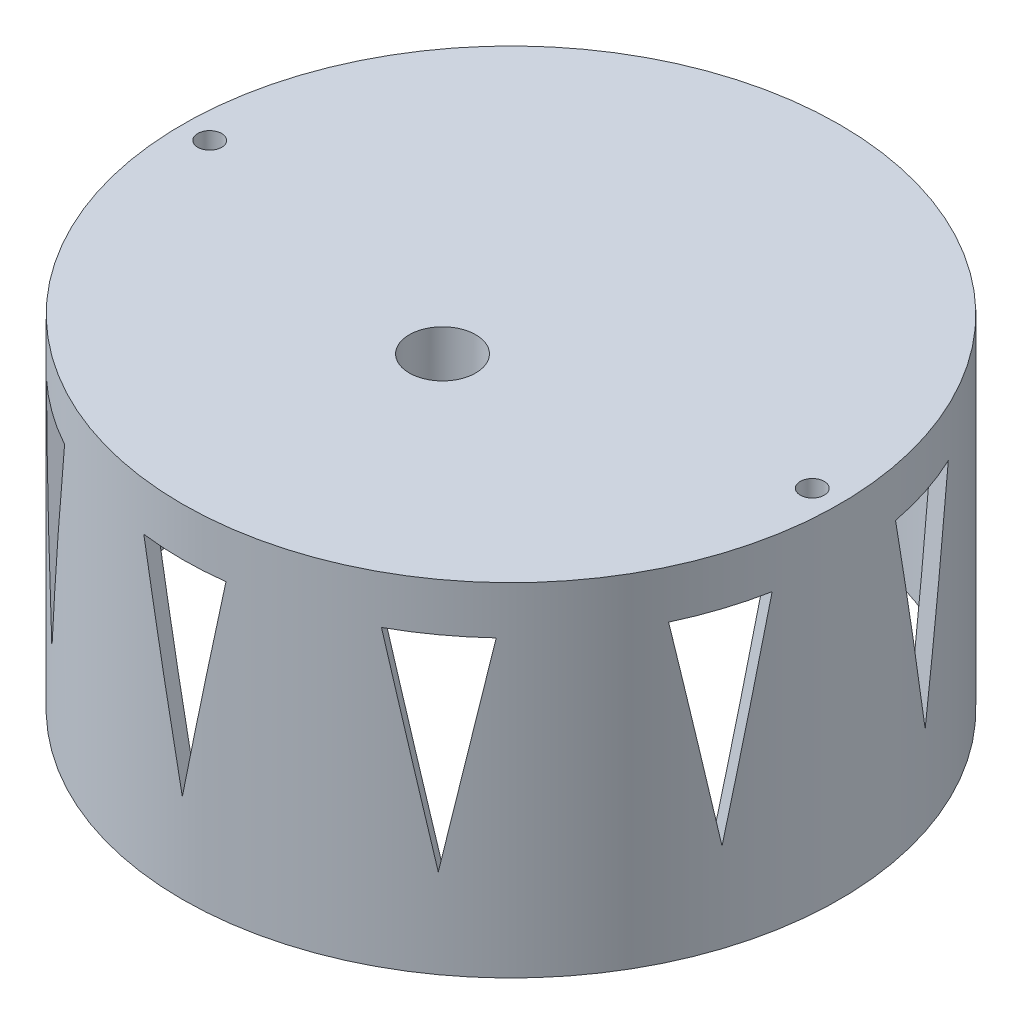
SolidWorks part; units mm, degrees
material "ABS"
ref_plane "Спереди" through (0, 0, 0) normal (0, 0, 1) x (1, 0, 0)
ref_plane "Сверху" through (0, 0, 0) normal (0, 1, 0) x (1, 0, 0)
ref_plane "Справа" through (0, 0, 0) normal (1, 0, 0) x (0, 0, -1)
sketch "Эскиз2" plane through (0, 0, 0) normal (0, 0, 1) x (1, 0, 0)
  line L0 (0, 0) -> (0, 74.988) construction
  line L1 (0, 0) -> (-48, 0)
  line L2 (-48, 0) -> (-48, -50)
  line L3 (-48, -50) -> (-46, -50)
  line L4 (-46, -50) -> (-46, -5.5)
  line L5 (-43, -2.5) -> (0, -2.5)
  line L6 (0, -2.5) -> (0, 0)
  arc A0 (-46, -5.5) -> (-43, -2.5) centre (-43, -5.5) cw
  dimension "D5" = 3
  dimension "D1" = 48
  dimension "D2" = 50
  dimension "D3" = 2
  dimension "D4" = 2.5
revolve "Основа" add sketch "Эскиз2" angle 360 about L0
sketch "Эскиз3" plane through (0, 0, 0) normal (0, 1, 0) x (1, 0, 0)
  line L0 (0, 48) -> (0, 0) construction
  circle A0 centre (0, 0) radius 48 construction
  circle A1 centre (0, -10) radius 4.85
  dimension "D1" = 9.7
  dimension "D2" = 10
extrude "Вырез под интерфейс" cut sketch "Эскиз3" against normal blind 38.7
sketch "Эскиз4" plane through (0, 0, 0) normal (0, 0, 1) x (1, 0, 0)
  line L0 (0, 0) -> (0, -22) construction
  line L1 (-6, -37) -> (6, -37) construction
  line L2 (-6, -37) -> (-6, -7) construction
  line L3 (-6, -7) -> (6, -7)
  line L4 (6, -37) -> (6, -7) construction
  line L5 (-6, -37) -> (6, -7) construction
  line L6 (-6, -7) -> (6, -37) construction
  line L7 (4.85, 0) -> (-4.85, 0) construction
  line L8 (-6, -7) -> (0, -37)
  line L9 (0, -37) -> (6, -7)
  line L10 (-48, -50) -> (48, -50) construction
  point P0 (0, -22)
  dimension "D1" = 30
  dimension "D2" = 12
  dimension "D3" = 7
  dimension "D4" = 22.62
  dimension "D5" = 13
  dimension "D6" = 78.69
extrude "Вырез облегчение" cut sketch "Эскиз4" against normal mid plane 141.7
pattern_circular "Массив вырезов" count 5 over 360 about axis through (0, 0, 0) along (0, 1, 0) of "Вырез облегчение"
sketch "Эскиз5" plane through (0, -2.5, 0) normal (0, -1, 0) x (1, 0, 0)
  circle A0 centre (0, 10) radius 4.85
  circle A1 centre (0, 10) radius 7.5
  dimension "D1" = 9.7
  dimension "D2" = 15
extrude "Наплыв интерфейса" add sketch "Эскиз5" along normal blind 5
sketch "Эскиз6" plane through (0, -2.5, 0) normal (0, -1, 0) x (1, 0, 0)
  line L0 (0, 0) -> (-35, 0) construction
  line L1 (0, 0) -> (0, 35) construction
  line L2 (0, 0) -> (35, 0) construction
  line L3 (-0.25, -34.9973) -> (0.25, -34.9973)
  line L5 (-0.25, -34.9973) -> (-0.25, 34.9991)
  line L6 (-0.25, 34.9991) -> (0.25, 34.9991)
  line L7 (0.25, -34.9973) -> (0.25, 34.9991)
  line L8 (-0.25, 0.0009) -> (0.25, 34.9991) construction
  line L9 (-0.25, 34.9991) -> (0.25, 0.0009) construction
  circle A0 centre (0, 0) radius 35 construction
  point P5 (0, 17.5)
  circle M2 centre (0, 10) radius 7.5
  dimension "D1" = 70
  dimension "D2" = 0.5
extrude "Ось" cut sketch "Эскиз6" against normal blind 0.1 contours L3 L7 L5 M2
fillet "Скругление2" radius 2 1 edges at (0, -7.5, 2.5)
sketch "Эскиз7" plane through (0, 0, 0) normal (0, 1, 0) x (1, 0, 0)
  circle A0 centre (0, 0) radius 44 construction
  circle A1 centre (44, 0) radius 1.75
  circle A2 centre (-44, 0) radius 1.75
  dimension "D1" = 88
  dimension "D2" = 3.5
  dimension "D3" = 3.5
extrude "Вырез-Вытянуть1" cut sketch "Эскиз7" against normal mid plane 8
